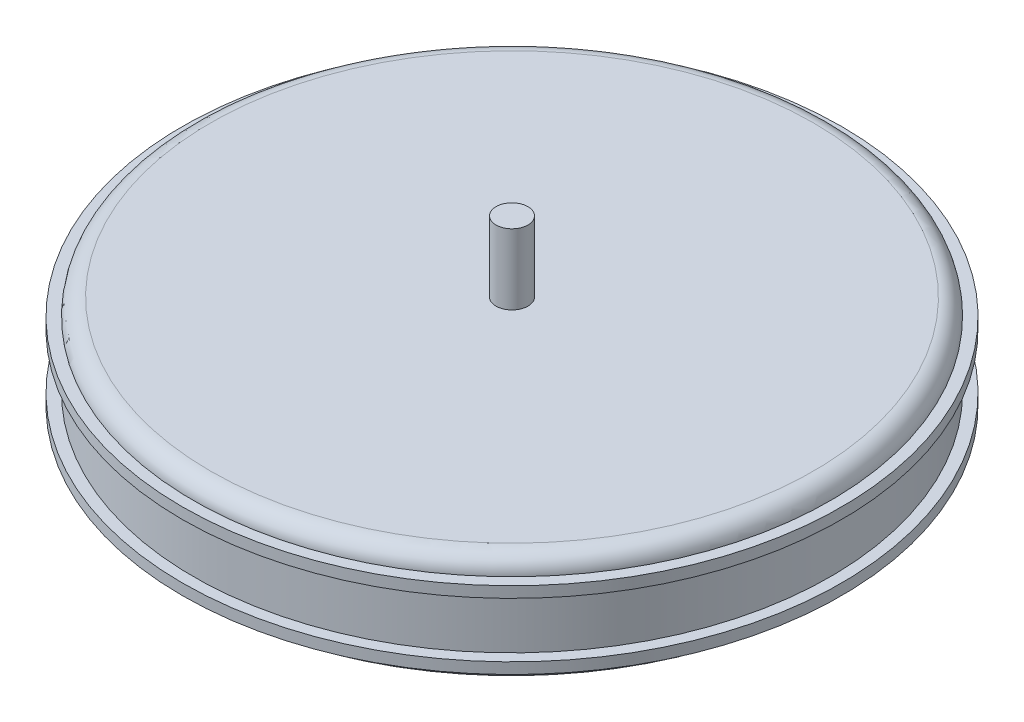
SolidWorks part; units mm, degrees
ref_plane "Front Plane" through (0, 0, 0) normal (0, 0, 1) x (1, 0, 0)
ref_plane "Top Plane" through (0, 0, 0) normal (0, 1, 0) x (1, 0, 0)
ref_plane "Right Plane" through (0, 0, 0) normal (1, 0, 0) x (0, 0, -1)
sketch "Sketch3" plane through (0, 0, 0) normal (1, 0, 0) x (0, 0, -1)
  line L0 (0, 49.7356) -> (0, -47.0145) construction
  line L1 (-7.25, 44.75) -> (-7.25, 12.75)
  line L2 (-7.25, 12.75) -> (-137.25, 12.75)
  line L3 (-145, 5) -> (-150, 5)
  line L4 (-150, 5) -> (-150, 0)
  line L5 (-150, 0) -> (-145, 0)
  line L6 (-145, 0) -> (-145, -25)
  line L7 (-145, -12.5) -> (21.5206, -12.5) construction
  line L8 (-150, -25) -> (-145, -25)
  line L9 (-150, -30) -> (-150, -25)
  line L10 (-145, -30) -> (-150, -30)
  line L11 (-7.25, -37.75) -> (-137.25, -37.75)
  line L12 (-7.25, -69.75) -> (-7.25, -37.75)
  line L13 (-7.25, 44.75) -> (0, 44.75)
  line L14 (-7.25, -69.75) -> (0, -69.75)
  line L15 (0, -69.75) -> (0, 44.75)
  arc A0 (-137.25, 12.75) -> (-145, 5) centre (-137.25, 5) ccw
  arc A1 (-137.25, -37.75) -> (-145, -30) centre (-137.25, -30) cw
  dimension "D1" = 12.5
  dimension "D2" = 5
  dimension "D3" = 5
  dimension "D4" = 5
  dimension "D5" = 130
  dimension "D6" = 300
  dimension "D7" = 14.5
  dimension "D8" = 32
  dimension "D9" = 14.5
revolve "Revolve1" add sketch "Sketch3" angle 360 about L15
